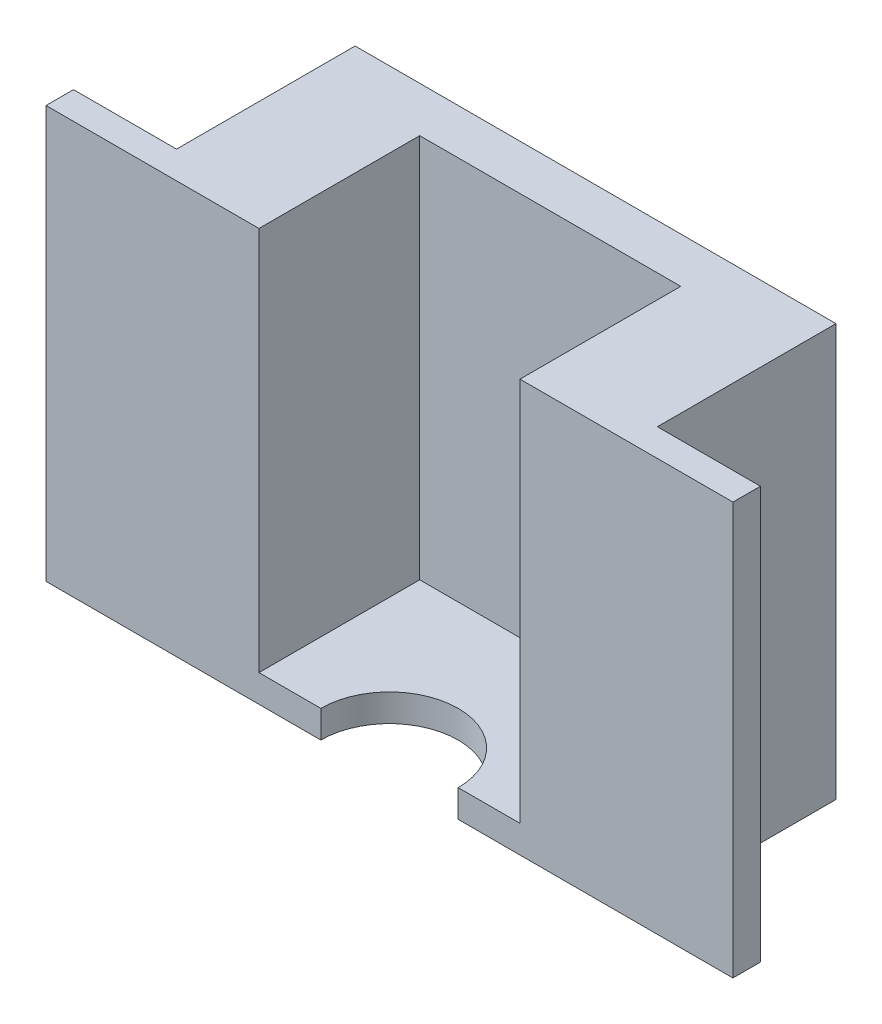
SolidWorks part; units mm, degrees
material "ABS"
ref_plane "Front" through (0, 0, 0) normal (0, 0, 1) x (1, 0, 0)
ref_plane "Top" through (0, 0, 0) normal (0, 1, 0) x (1, 0, 0)
ref_plane "Right" through (0, 0, 0) normal (1, 0, 0) x (0, 0, -1)
sketch "Эскиз1" plane through (0, 0, 0) normal (0, 0, 1) x (1, 0, 0)
  line L1 (-25, 15) -> (25, 15)
  line L2 (-25, 15) -> (-25, -15)
  line L3 (-25, -15) -> (25, -15)
  line L4 (25, 15) -> (25, -15)
  line L5 (-25, 15) -> (25, -15) construction
  line L6 (-25, -15) -> (25, 15) construction
  point P0 (0, 0)
  dimension "D1" = 50
  dimension "D2" = 30
extrude "Бобышка-Вытянуть1" add sketch "Эскиз1" along normal blind 15
sketch "Эскиз2" plane through (0, 15, 0) normal (0, 1, 0) x (1, 0, 0)
  line L0 (25, -15) -> (-25, -15) construction
  line L1 (-9.5, -15) -> (9.5, -15)
  line L2 (-9.5, -15) -> (-9.5, -3.3)
  line L3 (-9.5, -3.3) -> (9.5, -3.3)
  line L4 (9.5, -15) -> (9.5, -3.3)
  line L5 (-25, -15) -> (-25, 0) construction
  dimension "D1" = 19
  dimension "D2" = 11.7
  dimension "D3" = 15.5
extrude "Вырез-Вытянуть1" cut sketch "Эскиз2" against normal blind 28
sketch "Эскиз4" plane through (0, 15, 0) normal (0, 1, 0) x (1, 0, 0)
  line L1 (-25, 0) -> (-17.5, 0)
  line L2 (-25, 0) -> (-25, -13)
  line L3 (-25, -13) -> (-17.5, -13)
  line L4 (-17.5, 0) -> (-17.5, -13)
  dimension "D1" = 13
  dimension "D2" = 7.5
extrude "Вырез-Вытянуть3" cut sketch "Эскиз4" against normal blind 50
sketch "Эскиз5" plane through (0, 15, 0) normal (0, 1, 0) x (1, 0, 0)
  line L1 (25, 0) -> (17.5, 0)
  line L2 (25, 0) -> (25, -13)
  line L3 (25, -13) -> (17.5, -13)
  line L4 (17.5, 0) -> (17.5, -13)
  dimension "D1" = 7.5
  dimension "D2" = 13
extrude "Вырез-Вытянуть4" cut sketch "Эскиз5" against normal blind 50
sketch "Эскиз6" plane through (0, -15, 0) normal (0, -1, 0) x (1, 0, 0)
  line L0 (-5, 15) -> (5, 15)
  line L1 (-25, 15) -> (25, 15) construction
  arc A0 (-5, 15) -> (5, 15) centre (0, 15) ccw
  dimension "D2" = 5
  dimension "D1" = 10
  dimension "D3" = 25
extrude "Вырез-Вытянуть5" cut sketch "Эскиз6" against normal blind 50
